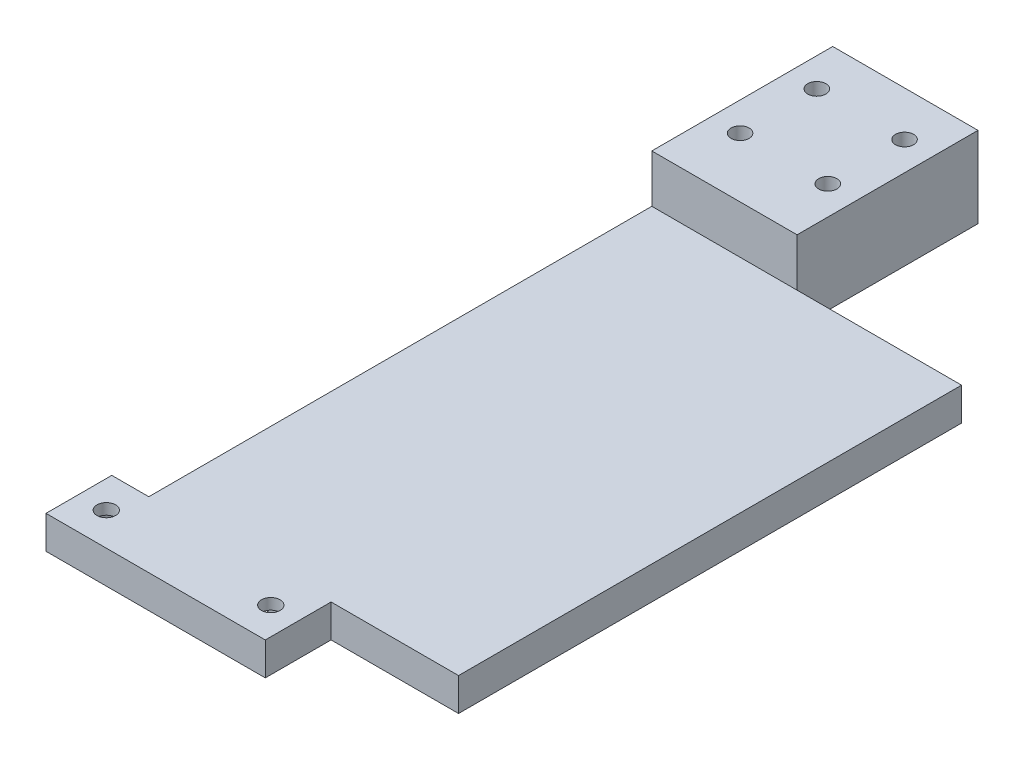
SolidWorks part; units mm, degrees
ref_plane "Front Plane" through (0, 0, 0) normal (0, 0, 1) x (1, 0, 0)
ref_plane "Top Plane" through (0, 0, 0) normal (0, 1, 0) x (1, 0, 0)
ref_plane "Right Plane" through (0, 0, 0) normal (1, 0, 0) x (0, 0, -1)
other "Configuration Table"
sketch "Sketch6" plane through (0, 0, 0) normal (0, 1, 0) x (1, 0, 0)
  line L3 (-13.25, 3.3) -> (-13.25, 0)
  line L8 (-13.25, 33) -> (-13.25, 3.3)
  line L9 (-13.25, 3.3) -> (13.25, 3.3) construction
  line L10 (13.25, 3.3) -> (13.25, 33)
  line L11 (13.25, 33) -> (-13.25, 33)
  line L12 (-13.25, 0) -> (13.25, 0)
  line L13 (13.25, 3.3) -> (13.25, 0)
  circle A5 centre (8, 10.85) radius 1.65
  circle A6 centre (8, 24.85) radius 1.65
  circle A7 centre (-8, 24.85) radius 1.65
  circle A9 centre (-8, 10.85) radius 1.65
  dimension "D1" = 26.5
extrude "Boss-Extrude3" add sketch "Sketch6" along normal blind 14.75
sketch "Sketch9" plane through (0, 0, 0) normal (0, 0, 1) x (1, 0, 0)
  line L0 (-13.25, 0) -> (13.25, 0) construction
  line L1 (-13.25, 0) -> (13.25, 0)
  line L2 (-13.25, 0) -> (-13.25, 6)
  line L3 (-13.25, 14.75) -> (-13.25, 0) construction
  line L4 (-13.25, 6) -> (13.25, 6)
  line L5 (13.25, 14.75) -> (13.25, 0) construction
  line L6 (13.25, 6) -> (13.25, 0)
  dimension "D1" = 6
extrude "Boss-Extrude4" add sketch "Sketch9" along normal blind 103.75
sketch "Sketch14" plane through (-13.25, 0, 0) normal (-1, 0, 0) x (0, 0, 1)
  line L0 (103.75, 6) -> (0, 6) construction
  line L1 (103.75, 0) -> (91.75, 0)
  line L2 (103.75, 0) -> (103.75, 6)
  line L3 (103.75, 6) -> (91.75, 6)
  line L4 (91.75, 0) -> (91.75, 6)
  dimension "D1" = 12
extrude "Boss-Extrude6" add sketch "Sketch14" against normal blind 33.25 and the other way blind 6.75
sketch "Sketch10" plane through (0, 6, 0) normal (0, 1, 0) x (1, 0, 0)
  line L0 (20, -103.75) -> (-20, -103.75) construction
  line L1 (20, -103.75) -> (-20, -103.75) construction
  line L3 (-13.25, -91.75) -> (-13.25, 0) construction
  line L4 (-13.25, -91.75) -> (13.25, -91.75) construction
  line L5 (13.25, -91.75) -> (13.25, 0) construction
  line L7 (-20, -97.75) -> (20, -97.75) construction
  line L8 (-20, -91.75) -> (-13.25, -91.75) construction
  line L9 (-20, -103.75) -> (-20, -91.75) construction
  line L10 (20, -103.75) -> (20, -91.75) construction
  circle A0 centre (-15, -97.75) radius 1.7
  circle A1 centre (15, -97.75) radius 1.7
  dimension "D2" = 3.4
  dimension "D3" = 5
  dimension "D1" = 5
extrude "Cut-Extrude1" cut sketch "Sketch10" against normal through all
sketch "Sketch11" plane through (0, 0, 0) normal (0, -1, 0) x (1, 0, 0)
  line L1 (-11.65, -29.5) -> (11.65, -29.5)
  line L2 (-11.65, -29.5) -> (-11.65, -6.2)
  line L3 (-11.65, -6.2) -> (11.65, -6.2)
  line L4 (11.65, -29.5) -> (11.65, -6.2)
  circle A2 centre (-8, -10.85) radius 1.65 construction
  circle A4 centre (8, -10.85) radius 1.65 construction
  circle A5 centre (-8, -24.85) radius 1.65 construction
  dimension "D3" = 3
  dimension "D4" = 3
  dimension "D1" = 2
  dimension "D2" = 2
extrude "Cut-Extrude2" cut sketch "Sketch11" against normal blind 4
sketch "Sketch12" plane through (0, 0, 0) normal (0, -1, 0) x (1, 0, 0)
  line L1 (-18.7, 102.45) -> (17.7728, 102.45)
  line L2 (-18.7, 102.45) -> (-18.7, 93.05)
  line L3 (-18.7, 93.05) -> (17.7728, 93.05)
  line L4 (17.7728, 102.45) -> (17.7728, 93.05)
  circle A0 centre (-15, 97.75) radius 1.7 construction
  circle A1 centre (15, 97.75) radius 1.7 construction
  dimension "D1" = 2
  dimension "D2" = 1.0728
  dimension "D3" = 3
  dimension "D4" = 3
extrude "Cut-Extrude3" cut sketch "Sketch12" against normal blind 4
sketch "Sketch15" plane through (13.25, 0, 0) normal (1, 0, 0) x (0, 0, -1)
  line L1 (-91.75, 6) -> (0, 6)
  line L2 (-91.75, 6) -> (-91.75, 0)
  line L3 (-91.75, 0) -> (0, 0)
  line L4 (0, 6) -> (0, 0)
extrude "Boss-Extrude8" add sketch "Sketch15" along normal blind 30
equation "\"D1@Boss-Extrude6\"= 26.50mm + 6.75"
equation "\"D1@Boss-Extrude4\"=91.00mm+12.75"
